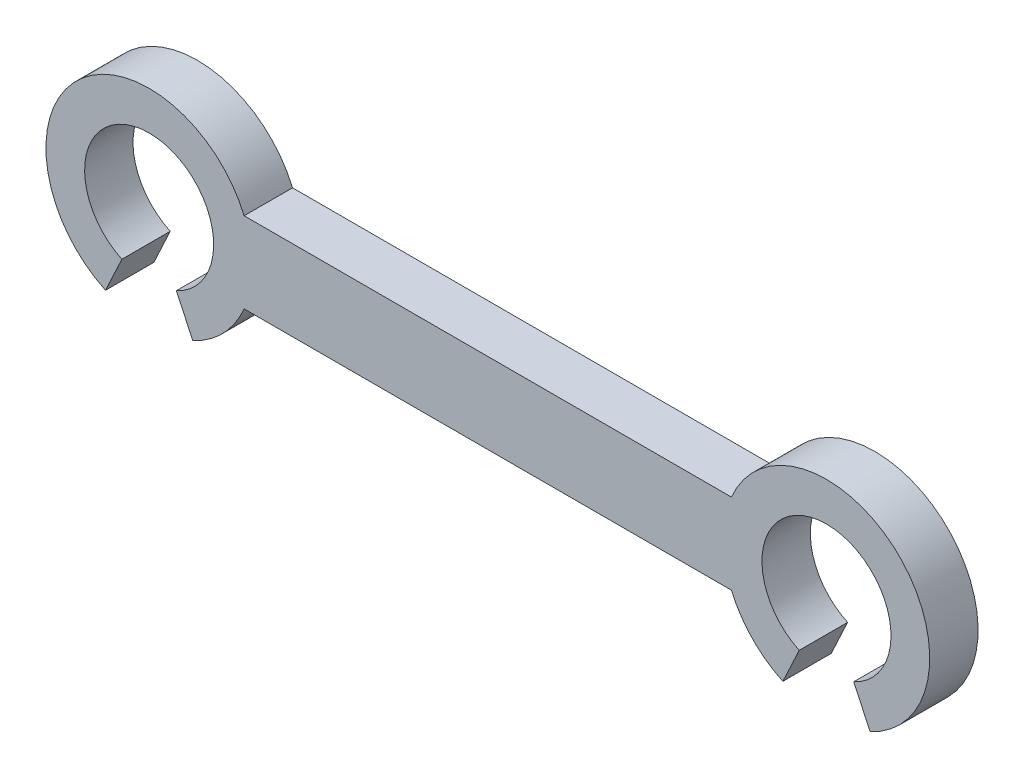
SolidWorks part; units mm, degrees
ref_plane "Plan de face" through (0, 0, 0) normal (0, 0, 1) x (1, 0, 0)
ref_plane "Plan de dessus" through (0, 0, 0) normal (0, 1, 0) x (1, 0, 0)
ref_plane "Plan de droite" through (0, 0, 0) normal (1, 0, 0) x (0, 0, -1)
sketch "Esquisse1" plane through (0, 0, 0) normal (0, 0, 1) x (1, 0, 0)
  line L0 (-10.5, 0) -> (-7.3221, -6.8151)
  line L1 (-10.5, -1.25) -> (10.5, -1.25)
  line L2 (-10.5, -1.25) -> (-10.5, 1.25)
  line L3 (-10.5, 1.25) -> (10.5, 1.25)
  line L4 (10.5, -1.25) -> (10.5, 1.25)
  line L5 (-10.5, -1.25) -> (10.5, 1.25) construction
  line L6 (-10.5, 1.25) -> (10.5, -1.25) construction
  line L7 (-10.5, 0) -> (-13.6779, -6.8151)
  line L8 (10.5, 0) -> (7.1126, -7.2643)
  line L9 (10.5, 0) -> (13.8874, -7.2643)
  circle A0 centre (10.5, 0) radius 2
  circle A1 centre (10.5, 0) radius 3.2
  circle A2 centre (-10.5, 0) radius 2
  circle A3 centre (-10.5, 0) radius 3.2
  point P0 (0, 0)
  dimension "D3" = 4
  dimension "D4" = 1.2
  dimension "D5" = 4
  dimension "D6" = 1.2
  dimension "D1" = 21
  dimension "D2" = 2.5
  dimension "D7" = 50
  dimension "D8" = 50
extrude "Boss.-Extru.1" add sketch "Esquisse1" along normal blind 1.5 contours L3 A3 L7 A2 | L1 A3 L3 A2 | A3 L1 A1 L3 | L3 A1 L1 A0 | L9 A1 L3 A0 | L0 A3 L1 A2 | L1 A1 L8 A0
